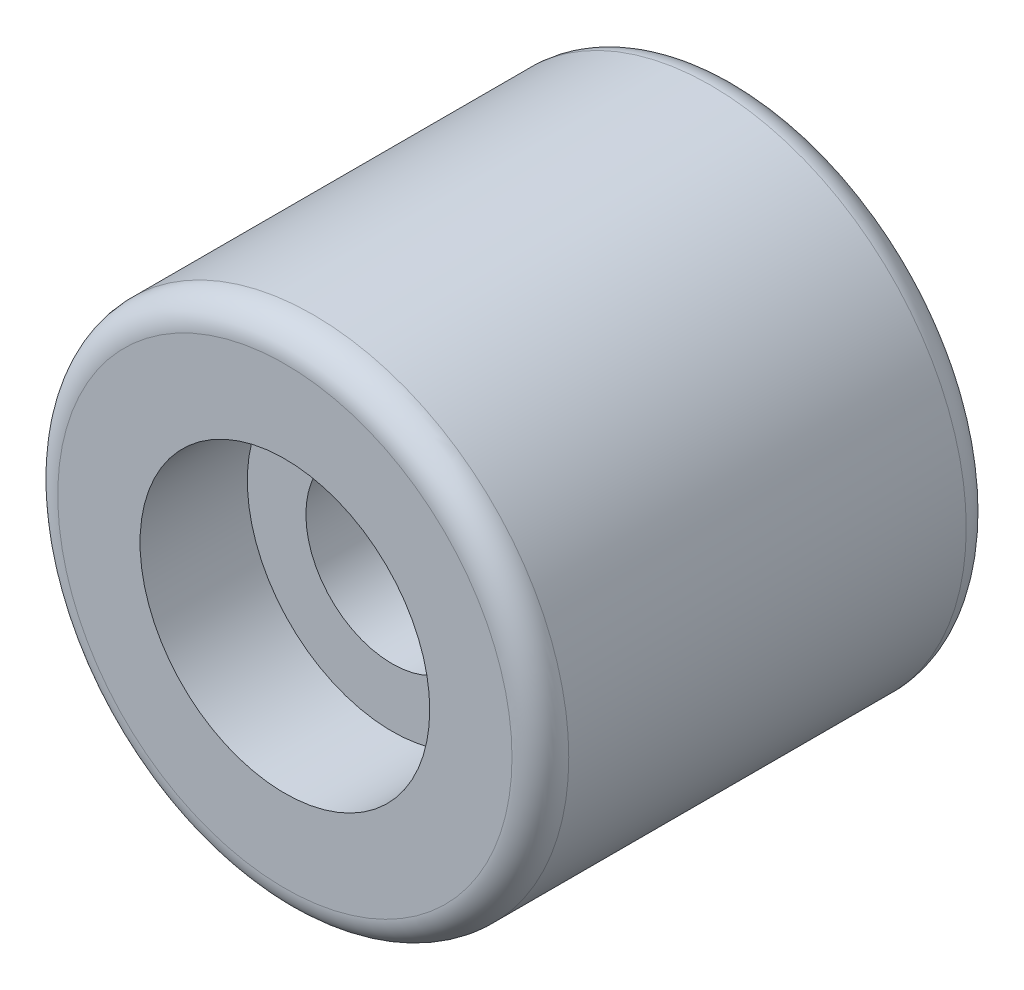
SolidWorks part; units mm, degrees
ref_plane "Front Plane" through (0, 0, 0) normal (0, 0, 1) x (1, 0, 0)
ref_plane "Top Plane" through (0, 0, 0) normal (0, 1, 0) x (1, 0, 0)
ref_plane "Right Plane" through (0, 0, 0) normal (1, 0, 0) x (0, 0, -1)
sketch "Sketch1" plane through (0, 0, 0) normal (0, 0, 1) x (1, 0, 0)
  circle A0 centre (0, 0) radius 7.1438
  circle A1 centre (0, 0) radius 2.413
  dimension "D1" = 4.826
  dimension "D2" = 14.2875
extrude "Boss-Extrude1" add sketch "Sketch1" along normal blind 12.7
sketch "Sketch2" plane through (0, 0, 12.7) normal (0, 0, 1) x (1, 0, 0)
  circle A0 centre (0, 0) radius 4.05
  dimension "D1" = 8.1
extrude "Cut-Extrude1" cut sketch "Sketch2" against normal blind 3
sketch "Sketch3" plane through (0, 0, 0) normal (0, 0, -1) x (-1, 0, 0)
  circle A0 centre (0, 0) radius 4.05
  dimension "D1" = 8.1
extrude "Cut-Extrude2" cut sketch "Sketch3" against normal blind 3
fillet "Fillet1" radius 0.7937 2 edges at (7.1438, 0, 12.7) (7.1438, 0, 0)
